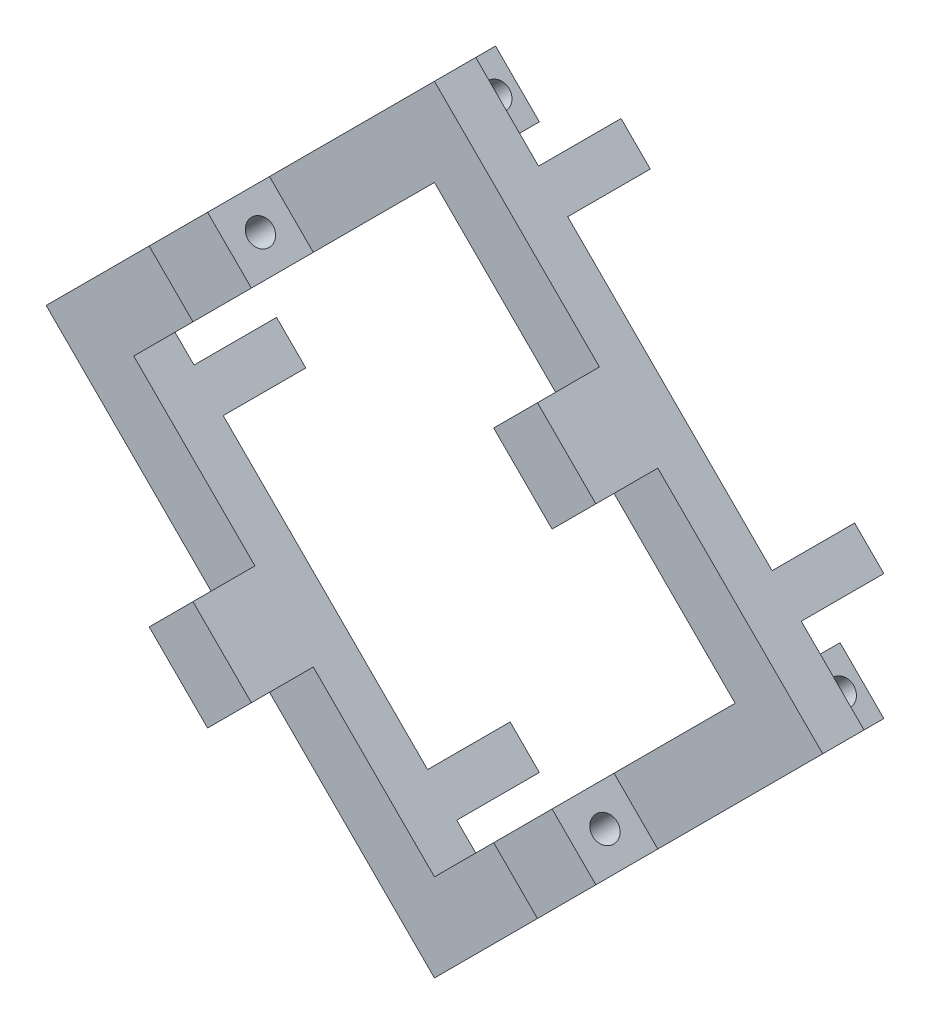
SolidWorks part; units mm, degrees
ref_plane "Alzado" through (0, 0, 0) normal (0, 0, 1) x (1, 0, 0)
ref_plane "Planta" through (0, 0, 0) normal (0, 1, 0) x (1, 0, 0)
ref_plane "Vista lateral" through (0, 0, 0) normal (1, 0, 0) x (0, 0, -1)
sketch "Croquis1" plane through (0, 0, 0) normal (0, 0, 1) x (1, 0, 0)
  line L0 (-71.7713, 22.2739) -> (-61.1647, 11.6673)
  line L1 (-71.7713, 22.2739) -> (-78.8424, 15.2028)
  line L2 (-61.1647, 11.6673) -> (-68.2358, 4.5962)
  line L3 (-78.8424, 15.2028) -> (-68.2358, 4.5962)
  line L4 (0, 0) -> (-41.7193, 41.7193) construction
  line L5 (-11.6673, 61.1647) -> (-4.5962, 68.2358)
  line L6 (-15.2028, 78.8424) -> (-4.5962, 68.2358)
  line L7 (-22.2739, 71.7713) -> (-15.2028, 78.8424)
  line L8 (-22.2739, 71.7713) -> (-11.6673, 61.1647)
  line L9 (22.2739, 71.7713) -> (11.6673, 61.1647)
  line L10 (22.2739, 71.7713) -> (15.2028, 78.8424)
  line L11 (15.2028, 78.8424) -> (4.5962, 68.2358)
  line L12 (11.6673, 61.1647) -> (4.5962, 68.2358)
  line L13 (61.1647, 11.6673) -> (68.2358, 4.5962)
  line L14 (78.8424, 15.2028) -> (68.2358, 4.5962)
  line L15 (71.7713, 22.2739) -> (78.8424, 15.2028)
  line L16 (71.7713, 22.2739) -> (61.1647, 11.6673)
  line L17 (71.7713, -22.2739) -> (61.1647, -11.6673)
  line L18 (71.7713, -22.2739) -> (78.8424, -15.2028)
  line L19 (78.8424, -15.2028) -> (68.2358, -4.5962)
  line L20 (61.1647, -11.6673) -> (68.2358, -4.5962)
  line L21 (11.6673, -61.1647) -> (4.5962, -68.2358)
  line L22 (15.2028, -78.8424) -> (4.5962, -68.2358)
  line L23 (22.2739, -71.7713) -> (15.2028, -78.8424)
  line L24 (22.2739, -71.7713) -> (11.6673, -61.1647)
  line L25 (-22.2739, -71.7713) -> (-11.6673, -61.1647)
  line L26 (-22.2739, -71.7713) -> (-15.2028, -78.8424)
  line L27 (-15.2028, -78.8424) -> (-4.5962, -68.2358)
  line L28 (-11.6673, -61.1647) -> (-4.5962, -68.2358)
  line L29 (-61.1647, -11.6673) -> (-68.2358, -4.5962)
  line L30 (-78.8424, -15.2028) -> (-68.2358, -4.5962)
  line L31 (-71.7713, -22.2739) -> (-78.8424, -15.2028)
  line L32 (-71.7713, -22.2739) -> (-61.1647, -11.6673)
  circle A0 centre (0, 0) radius 54 construction
  point P6 (-66.468, 16.9706)
  point P36 (0, 0)
  dimension "D3" = 108
  dimension "D1" = 15
  dimension "D2" = 10
  dimension "D4" = 4.5962
  dimension "D5" = 71.7713
  dimension "D6" = 22.2739
extrude "Saliente-Extruir1" add sketch "Croquis1" along normal blind 20
sketch "Croquis2" plane through (0, 0, 20) normal (0, 0, 1) x (1, 0, 0)
  line L5 (0, 72.832) -> (72.832, 0)
  line L6 (4.5962, 68.2358) -> (11.6673, 61.1647) construction
  line L7 (0, 94.0452) -> (94.0452, 0)
  line L8 (78.8424, 15.2028) -> (71.7713, 22.2739) construction
  line L9 (72.832, 0) -> (0, -72.832)
  line L10 (94.0452, 0) -> (0, -94.0452)
  line L11 (0, -72.832) -> (-72.832, 0)
  line L12 (0, -94.0452) -> (-94.0452, 0)
  line L13 (-72.832, 0) -> (0, 72.832)
  line L14 (-94.0452, 0) -> (0, 94.0452)
  circle A0 centre (0, 0) radius 72.832 construction
  point P26 (0, 0)
  dimension "D1" = 4
extrude "Saliente-Extruir2" add sketch "Croquis2" along normal blind 10
sketch "Croquis4" plane through (47.0226, 47.0226, 0) normal (0.7071, 0.7071, 0) x (0, 0, -1)
  line L0 (0, -45) -> (0, -35) construction
  line L1 (-20, -45) -> (0, -45) construction
  circle A0 centre (-5, -40) radius 3
  dimension "D1" = 6
  dimension "D2" = 5
  dimension "D3" = 5
sketch "Croquis7" plane through (31.8198, 31.8198, 0) normal (0.7071, 0.7071, 0) x (0, 0, -1)
  line L0 (0, -66.5) -> (0, -51.5) construction
  line L2 (-20, -66.5) -> (0, -66.5) construction
  circle A0 centre (-5, -59) radius 3
  dimension "D1" = 6
  dimension "D2" = 5
  dimension "D3" = 7.5
extrude "Cortar-Extruir2" cut sketch "Croquis7" against normal up to surface (80 mm away)
sketch "Croquis8" plane through (31.8198, -31.8198, 0) normal (0.7071, -0.7071, 0) x (0, 0, -1)
  line L0 (-20, 51.5) -> (0, 51.5) construction
  line L1 (0, 51.5) -> (0, 66.5) construction
  circle A0 centre (-5, 59) radius 3
  dimension "D1" = 6
  dimension "D2" = 7.5
  dimension "D3" = 5
extrude "Cortar-Extruir3" cut sketch "Croquis8" against normal up to surface (10 mm away) up to face at (66.468, 16.9706, 10)
ref_plane "Plano3" through (0, 0, 20) normal (0, 0, 1) x (1, 0, 0)
ref_plane "Plano4" through (0, 0, 0) normal (0.7071, -0.7071, 0) x (0, 0, -1)
mirror "Simetría3" about plane through (0, 0, 0) normal (0.7071, -0.7071, 0) of "Cortar-Extruir2", "Cortar-Extruir3"
ref_plane "Plano5" through (0, 0, 0) normal (-0.7071, -0.7071, 0) x (-0.7071, 0.7071, 0)
mirror "Simetría4" about plane through (0, 0, 0) normal (-0.7071, -0.7071, 0) of "Simetría3", "Cortar-Extruir2", "Cortar-Extruir3"
sketch "Croquis10" plane through (0, 0, 30) normal (0, 0, 1) x (1, 0, 0)
  line L0 (29.3449, 43.4871) -> (39.9515, 54.0937)
  line L1 (29.3449, 43.4871) -> (43.4871, 29.3449)
  line L2 (39.9515, 54.0937) -> (54.0937, 39.9515)
  line L3 (43.4871, 29.3449) -> (54.0937, 39.9515)
  line L4 (72.832, 0) -> (0, 72.832) construction
  line L5 (94.0452, 0) -> (0, 94.0452) construction
  line L6 (0, 0) -> (36.416, 36.416) construction
  line L7 (0, 0) -> (-36.416, 36.416) construction
  line L10 (0, 72.832) -> (-72.832, 0) construction
  line L11 (43.4871, -29.3449) -> (54.0937, -39.9515)
  line L12 (43.4871, -29.3449) -> (29.3449, -43.4871)
  line L13 (29.3449, -43.4871) -> (39.9515, -54.0937)
  line L14 (54.0937, -39.9515) -> (39.9515, -54.0937)
  line L15 (-29.3449, -43.4871) -> (-39.9515, -54.0937)
  line L16 (-29.3449, -43.4871) -> (-43.4871, -29.3449)
  line L17 (-43.4871, -29.3449) -> (-54.0937, -39.9515)
  line L18 (-39.9515, -54.0937) -> (-54.0937, -39.9515)
  line L19 (-43.4871, 29.3449) -> (-54.0937, 39.9515)
  line L20 (-43.4871, 29.3449) -> (-29.3449, 43.4871)
  line L21 (-29.3449, 43.4871) -> (-39.9515, 54.0937)
  line L22 (-54.0937, 39.9515) -> (-39.9515, 54.0937)
  circle A0 centre (0, 0) radius 51.5 construction
  point P8 (36.416, 36.416)
  point P31 (0, 0)
  dimension "D1" = 90
  dimension "D2" = 90
  dimension "D3" = 20
  dimension "D4" = 4
extrude "Saliente-Extruir3" add sketch "Croquis10" along normal blind 15
sketch "Croquis11" plane through (7.0711, -7.0711, 0) normal (0.7071, -0.7071, 0) x (0, 0, -1)
  line L0 (0, 0) -> (-45, 0) construction
  line L1 (-45, -10) -> (-45, 10) construction
  line L2 (-45, 51.5) -> (-45, 66.5) construction
  line L3 (-45, 66.5) -> (-30, 66.5) construction
  circle A0 centre (-37.5, 59) radius 3
  circle A1 centre (-37.5, -59) radius 3
  dimension "D1" = 6
  dimension "D2" = 7.5
  dimension "D3" = 7.5
extrude "Cortar-Extruir4" cut sketch "Croquis11" against normal through all
sketch "Croquis13" plane through (-7.0711, -7.0711, 0) normal (-0.7071, -0.7071, 0) x (0, 0, 1)
  line L0 (0, 0) -> (45, 0) construction
  line L1 (45, 10) -> (45, -10) construction
  line L2 (45, -51.5) -> (45, -66.5) construction
  line L3 (45, -66.5) -> (30, -66.5) construction
  circle A0 centre (37.5, -59) radius 3
  circle A1 centre (37.5, 59) radius 3
  dimension "D1" = 6
  dimension "D2" = 7.5
  dimension "D3" = 7.5
extrude "Cortar-Extruir5" cut sketch "Croquis13" against normal through all
